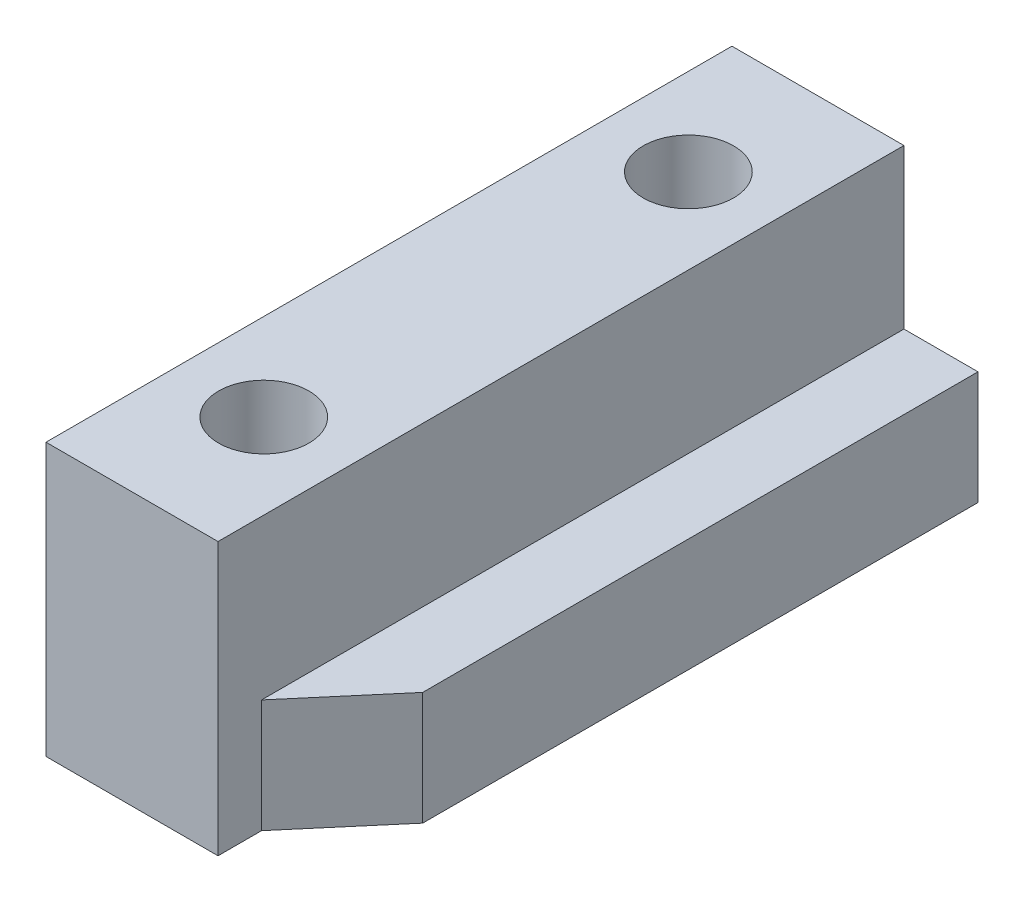
SolidWorks part; units mm, degrees
ref_plane "Front Plane" through (0, 0, 0) normal (0, 0, 1) x (1, 0, 0)
ref_plane "Top Plane" through (0, 0, 0) normal (0, 1, 0) x (1, 0, 0)
ref_plane "Right Plane" through (0, 0, 0) normal (1, 0, 0) x (0, 0, -1)
sketch "Sketch1" plane through (0, 0, 0) normal (0, 0, 1) x (1, 0, 0)
  line L0 (0, 0) -> (0, 12.5)
  line L1 (0, 12.5) -> (7.9, 12.5)
  line L2 (7.9, 12.5) -> (7.9, 5.2)
  line L3 (7.9, 5.2) -> (11.3, 5.2)
  line L4 (11.3, 5.2) -> (11.3, 0)
  line L5 (11.3, 0) -> (0, 0)
  dimension "D1" = 11.3
  dimension "D2" = 12.5
  dimension "D3" = 7.9
  dimension "D4" = 5.2
extrude "Boss-Extrude1" add sketch "Sketch1" against normal blind 31.5
sketch "Sketch2" plane through (0, 12.5, 0) normal (0, 1, 0) x (1, 0, 0)
  line L0 (7.9, 31.5) -> (0, 31.5) construction
  line L1 (0, 31.5) -> (0, 0) construction
  line L2 (7.9, 0) -> (0, 0) construction
  circle A0 centre (4, 6) radius 2.075
  circle A1 centre (4, 25.5) radius 2.075
  dimension "D1" = 4.15
  dimension "D2" = 6
  dimension "D3" = 4
  dimension "D4" = 6
extrude "Cut-Extrude1" cut sketch "Sketch2" against normal blind 7
sketch "Sketch3" plane through (0, 0, 0) normal (0, -1, 0) x (1, 0, 0)
  line L1 (11.3, -31.5) -> (11.3, 0) construction
  line L2 (0, 0) -> (11.3, 0) construction
  line L3 (7.9, -31.5) -> (7.9, 0) construction
  line L4 (7.9, -2) -> (7.9, 0)
  line L5 (11.3, -6) -> (7.9, -2)
  line L6 (7.9, 0) -> (11.3, 0)
  line L7 (11.3, 0) -> (11.3, -6)
  dimension "D1" = 4
  dimension "D2" = 2
extrude "Cut-Extrude2" cut sketch "Sketch3" against normal blind 10
move or copy body "Body-Move/Copy1" [suppressed] bodies to move or copy 103 parameters "D1"=0, "D2"=0, "D3"=0
